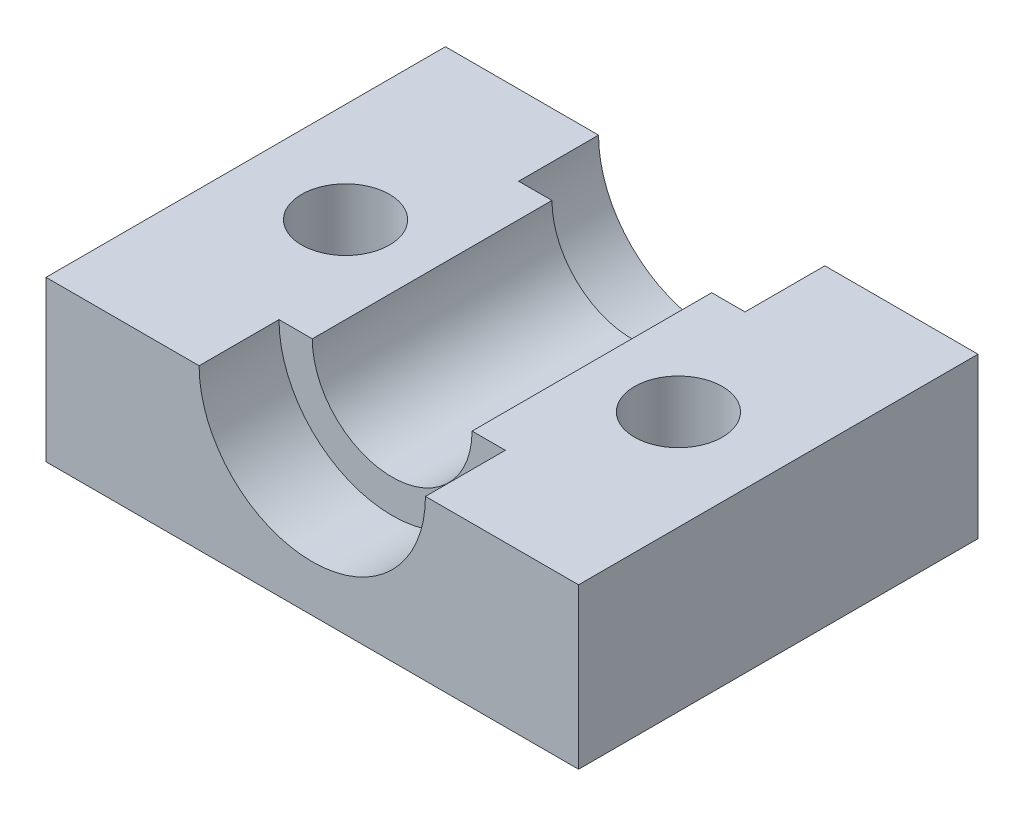
SolidWorks part; units mm, degrees
material "Д16Т ГОСТ 4784-74"
ref_plane "Спереди" through (0, 0, 0) normal (0, 0, 1) x (1, 0, 0)
ref_plane "Сверху" through (0, 0, 0) normal (0, 1, 0) x (1, 0, 0)
ref_plane "Справа" through (0, 0, 0) normal (1, 0, 0) x (0, 0, -1)
sketch "Эскиз1" plane through (0, 0, 0) normal (0, 0, 1) x (1, 0, 0)
  line L0 (28.5, 12) -> (40, 12)
  line L1 (0, 0) -> (40, 0)
  line L2 (0, 0) -> (0, 12)
  line L3 (0, 12) -> (11.5, 12)
  line L4 (40, 0) -> (40, 12)
  line L5 (11.5, 12) -> (28.5, 12) construction
  arc A0 (11.5, 12) -> (28.5, 12) centre (20, 12) ccw
  dimension "D1" = 17
  dimension "D2" = 12
  dimension "D3" = 40
extrude "Бобышка-Вытянуть1" add sketch "Эскиз1" along normal blind 24 and the other way blind 6
sketch "Эскиз3" plane through (0, 0, 0) normal (0, 0, 1) x (1, 0, 0)
  line L0 (11.5, 12) -> (14, 12)
  line L1 (26, 12) -> (28.5, 12)
  arc A0 (14, 12) -> (26, 12) centre (20, 12) ccw
  arc A1 (11.5, 12) -> (28.5, 12) centre (20, 12) ccw
  arc A2 (11.5, 12) -> (28.5, 12) centre (20, 12) ccw construction
  dimension "D1" = 12
extrude "Бобышка-Вытянуть2" add sketch "Эскиз3" along normal blind 18
hole_wizard "Цековка для  винта с внутренним шестигранником M61" positions "Эскиз9" profile "Эскиз10" counterbore size "M6" standard "DIN" end condition through all
sketch "Эскиз9" plane through (0, 0, 0) normal (0, -1, 0) x (1, 0, 0)
  line L0 (20, 24) -> (20, -6) construction
  line L1 (0, 24) -> (40, 24) construction
  line L2 (0, -6) -> (40, -6) construction
  line L5 (20, 9) -> (7.5, 9)
  point P0 (7.5, 9)
  point P16 (32.5, 9)
  dimension "D1" = 25
sketch "Эскиз10" plane through (7.5, 0, 9) normal (1, 0, 0) x (0, 0, -1)
  line L0 (0, 0) -> (0, 12)
  line L1 (0, 12) -> (3.3, 12)
  line L3 (3.3, 12) -> (3.3, 6.4)
  line L4 (3.3, 6.4) -> (5.5, 6.4)
  line L5 (5.5, 6.4) -> (5.5, 0)
  line L7 (5.5, 0) -> (0, 0)
  line L11 (0, -6.35) -> (0, 107.95) construction
  dimension "Диаметр сквозного отверстия" = 6.6
  dimension "Глубина сквозного отверстия" = 12
  dimension "Диаметр цековки" = 11
  dimension "Глубина цековки" = 6.4
